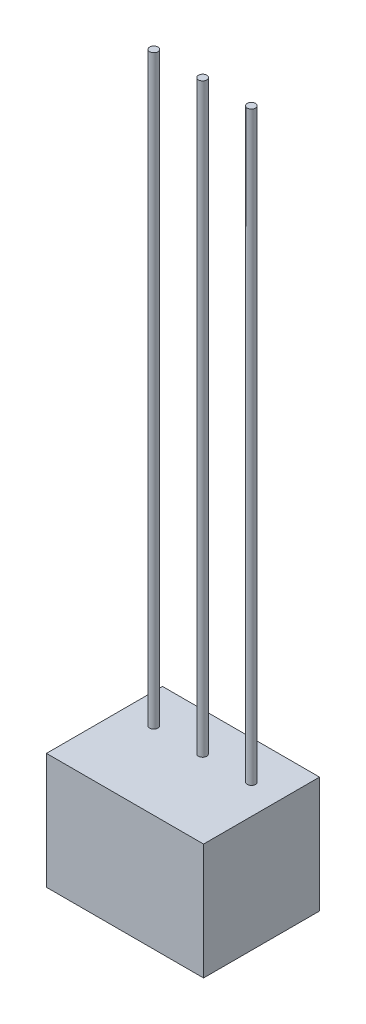
SolidWorks part; units mm, degrees
ref_plane "Front Plane" through (0, 0, 0) normal (0, 0, 1) x (1, 0, 0)
ref_plane "Top Plane" through (0, 0, 0) normal (0, 1, 0) x (1, 0, 0)
ref_plane "Right Plane" through (0, 0, 0) normal (1, 0, 0) x (0, 0, -1)
sketch "Sketch1" plane through (0, 0, 0) normal (0, 0, 1) x (1, 0, 0)
  line L1 (0, 0) -> (4.09, 0)
  line L2 (0, 0) -> (0, 3.02)
  line L3 (0, 3.02) -> (4.09, 3.02)
  line L4 (4.09, 0) -> (4.09, 3.02)
  dimension "D2" = 4.09
  dimension "D3" = 3.02
extrude "Boss-Extrude1" add sketch "Sketch1" along normal blind 3.02 contours L3 L4 L1 L2
sketch "Sketch2" plane through (0, 3.02, 0) normal (0, 1, 0) x (1, 0, 0)
  line L0 (0, 0) -> (4.09, 0) construction
  circle A0 centre (0.775, -1) radius 0.1075
  circle A1 centre (2.045, -1) radius 0.1075
  circle A2 centre (3.315, -1) radius 0.1075
  point P4 (2.045, 0)
  dimension "D3" = 0.215
  dimension "D1" = 1
  dimension "D2" = 3
extrude "Boss-Extrude2" add sketch "Sketch2" along normal blind 15.25
sketch3d "3DSketch2"
  line L0 (2.045, 1.51, 0) -> (2.045, 1.51, 4.52)
  line L4 (4.09, 1.51, 3.02) -> (0, 1.51, 3.02) construction
  line L5 (4.09, 0, 3.02) -> (4.09, 3.02, 3.02) construction
  line L6 (0, 0, 3.02) -> (0, 3.02, 3.02) construction
  point P8 (2.045, 1.51, 3.02)
  point P9 (2.045, 1.51, 3.02)
  dimension "D1" = 1.51
  dimension "D2" = 1.5
